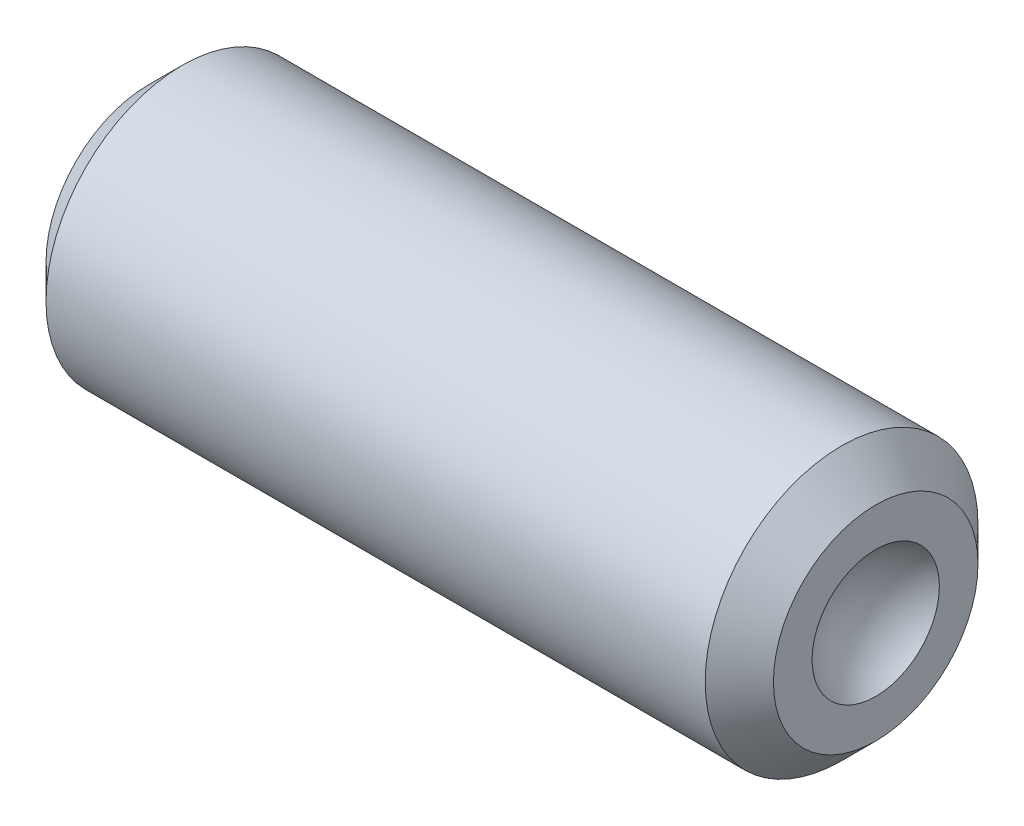
SolidWorks part; units mm, degrees
ref_plane "Front Plane" through (0, 0, 0) normal (0, 0, 1) x (1, 0, 0)
ref_plane "Top Plane" through (0, 0, 0) normal (0, 1, 0) x (1, 0, 0)
ref_plane "Right Plane" through (0, 0, 0) normal (1, 0, 0) x (0, 0, -1)
sketch "Sketch1" plane through (0, 0, 0) normal (0, 0, 1) x (1, 0, 0)
  line L0 (0, 0) -> (0, 1.125)
  line L1 (0, 1.125) -> (0.375, 1.5)
  line L2 (0.375, 1.5) -> (7.625, 1.5)
  line L3 (7.625, 1.5) -> (8, 1.125)
  line L4 (0, 0) -> (7.625, 0) construction
  line L5 (0.375, 1.5) -> (0.375, 1.125) construction
  line L6 (0.375, 1.125) -> (0.375, 0.75) construction
  line L7 (0.375, 0.75) -> (0.375, 0.375) construction
  line L8 (0.375, 0.375) -> (0.375, 0) construction
  line L9 (0.375, 1.125) -> (0, 1.125) construction
  line L10 (7.625, 1.5) -> (7.625, 0) construction
  line L11 (8, 1.125) -> (8, 0.7)
  line L12 (0, 0) -> (7.625, 0)
  arc A0 (7.625, 0) -> (8, 0.7) centre (8.4658, 0) cw
  dimension "D1" = 45
  dimension "D2" = 3
  dimension "D3" = 8
  dimension "D4" = 1.4
revolve "Revolve1" add sketch "Sketch1" angle 360 about L12
sketch "Sketch2" plane through (0, 0, 0) normal (-1, 0, 0) x (0, 0, 1)
  line L1 (0, 0.866) -> (-0.75, 0.433)
  line L2 (-0.75, 0.433) -> (-0.75, -0.433)
  line L3 (-0.75, -0.433) -> (0, -0.866)
  line L4 (0, -0.866) -> (0.75, -0.433)
  line L5 (0.75, -0.433) -> (0.75, 0.433)
  line L6 (0.75, 0.433) -> (0, 0.866)
  circle A0 centre (0, 0) radius 0.75 construction
  dimension "D1" = 1.5
extrude "Cut-Extrude1" cut sketch "Sketch2" against normal offset from surface (6 mm away) 2 up to face at (8, -1.125, 0)
